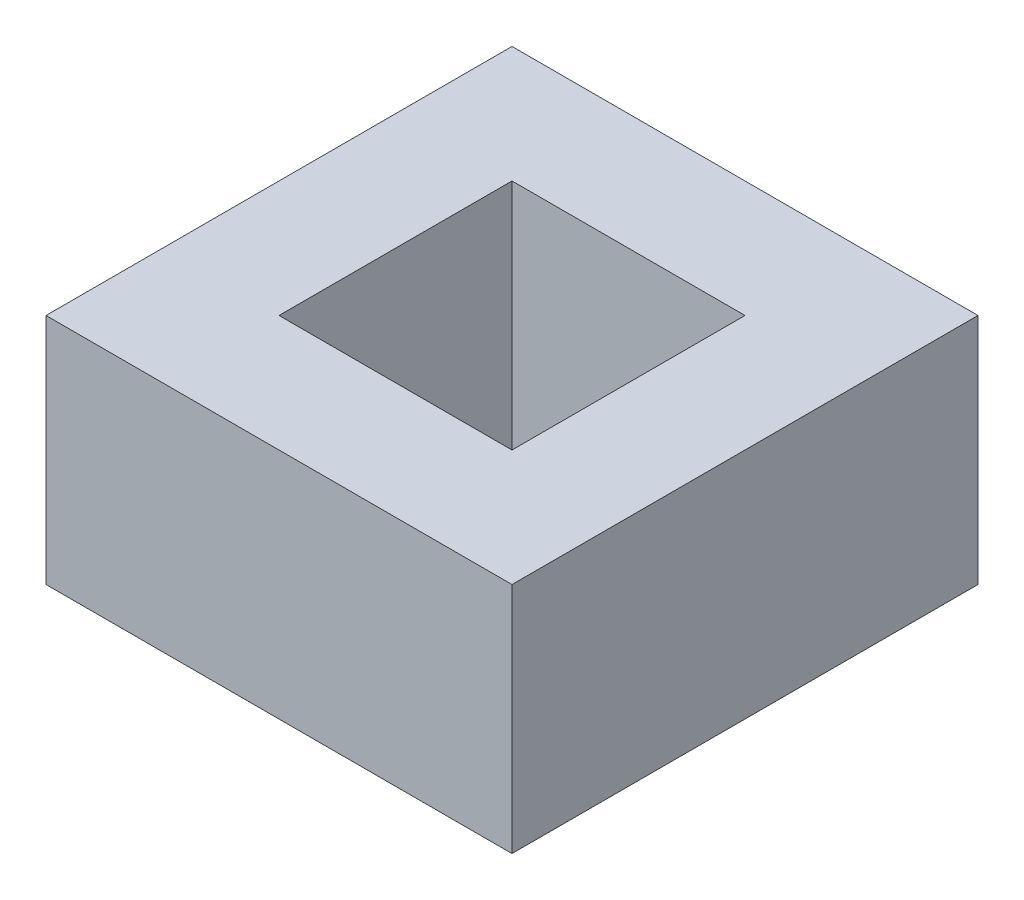
SolidWorks part; units mm, degrees
ref_plane "Front Plane" through (0, 0, 0) normal (0, 0, 1) x (1, 0, 0)
ref_plane "Top Plane" through (0, 0, 0) normal (0, 1, 0) x (1, 0, 0)
ref_plane "Right Plane" through (0, 0, 0) normal (1, 0, 0) x (0, 0, -1)
sketch "Sketch1" plane through (0, 0, 0) normal (0, 1, 0) x (1, 0, 0)
  line L1 (0, 0) -> (-40, 0)
  line L2 (0, 0) -> (0, -40)
  line L3 (0, -40) -> (-40, -40)
  line L4 (-40, 0) -> (-40, -40)
  line L5 (-10, -10) -> (-30, -10)
  line L6 (-10, -10) -> (-10, -30)
  line L7 (-10, -30) -> (-30, -30)
  line L8 (-30, -10) -> (-30, -30)
  dimension "D1" = 40
  dimension "D2" = 40
  dimension "D3" = 10
  dimension "D4" = 20
  dimension "D5" = 20
  dimension "D6" = 10
extrude "Boss-Extrude1" add sketch "Sketch1" along normal blind 20
